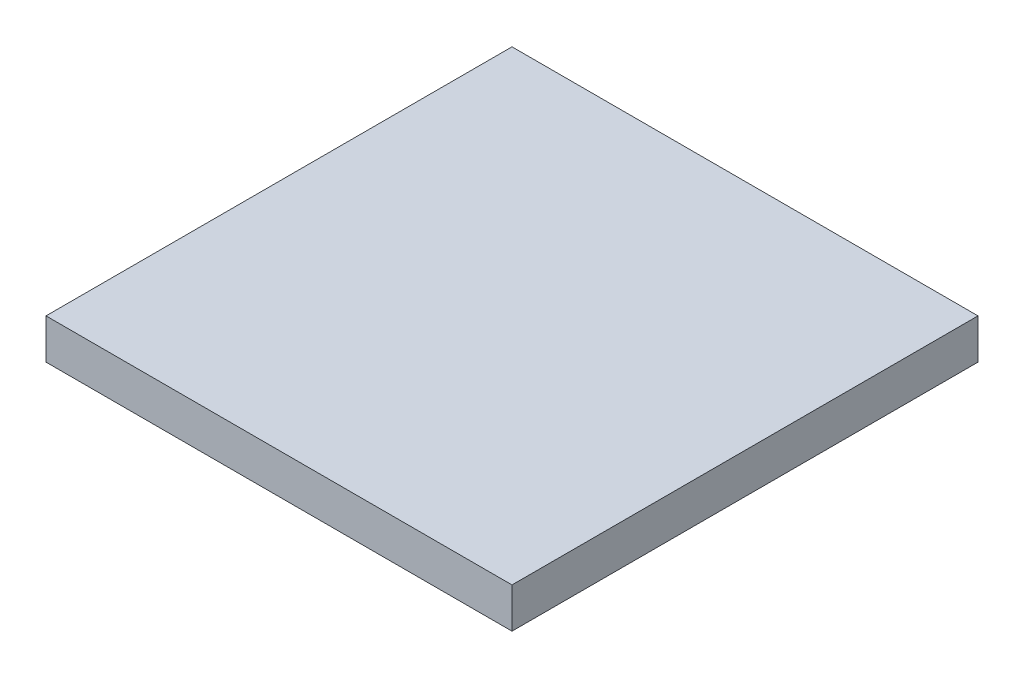
SolidWorks part; units mm, degrees
material "Wasser"
ref_plane "Ebene vorne" through (0, 0, 0) normal (0, 0, 1) x (1, 0, 0)
ref_plane "Ebene oben" through (0, 0, 0) normal (0, 1, 0) x (1, 0, 0)
ref_plane "Ebene rechts" through (0, 0, 0) normal (1, 0, 0) x (0, 0, -1)
sketch "Skizze1" plane through (0, 0, 0) normal (0, 1, 0) x (1, 0, 0)
  line L1 (-1044.5377, 452.7243) -> (1955.4623, 452.7243)
  line L2 (-1044.5377, 452.7243) -> (-1044.5377, -2547.2757)
  line L3 (-1044.5377, -2547.2757) -> (1955.4623, -2547.2757)
  line L4 (1955.4623, 452.7243) -> (1955.4623, -2547.2757)
  dimension "D1" = 3000
  dimension "D2" = 3000
extrude "Aufsatz-Linear austragen1" add sketch "Skizze1" along normal blind 258
